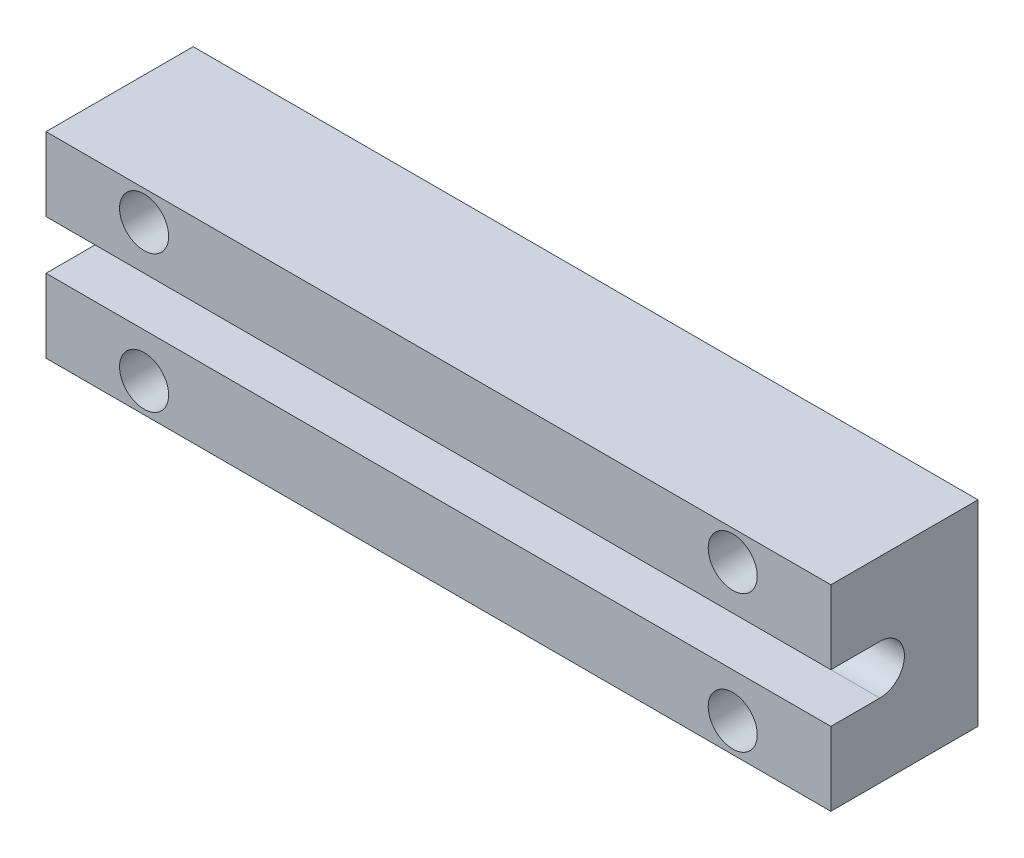
SolidWorks part; units mm, degrees
ref_plane "Plan de face" through (0, 0, 0) normal (0, 0, 1) x (1, 0, 0)
ref_plane "Plan de dessus" through (0, 0, 0) normal (0, 1, 0) x (1, 0, 0)
ref_plane "Plan de droite" through (0, 0, 0) normal (1, 0, 0) x (0, 0, -1)
sketch "Esquisse1" plane through (0, 0, 0) normal (0, 0, 1) x (1, 0, 0)
  line L1 (0, 0) -> (-80, 0)
  line L2 (0, 0) -> (0, 20)
  line L3 (0, 20) -> (-80, 20)
  line L4 (-80, 0) -> (-80, 20)
  dimension "D1" = 80
  dimension "D2" = 20
extrude "Boss.-Extru.1" add sketch "Esquisse1" along normal blind 15
sketch "Esquisse2" plane through (0, 0, 0) normal (1, 0, 0) x (0, 0, -1)
  line L0 (-15, 10) -> (-10, 10) construction
  line L1 (-15, 0) -> (-15, 20) construction
  line L2 (0, 0) -> (0, 20) construction
  line L3 (-7.5, 10) -> (0, 10) construction
  line L4 (-15, 7.5) -> (-10, 7.5)
  line L5 (-15, 7.5) -> (-15, 12.5)
  line L6 (-15, 12.5) -> (-10, 12.5)
  arc A0 (-10, 7.5) -> (-10, 12.5) centre (-10, 10) ccw
  dimension "D1" = 2.5
  dimension "D2" = 2.5
extrude "Enlèv. mat.-Extru.1" cut sketch "Esquisse2" against normal blind 94
sketch "Esquisse3" plane through (0, 0, 0) normal (0, 0, -1) x (-1, 0, 0)
  line L0 (40, 20) -> (40, 0) construction
  line L1 (0, 20) -> (80, 20) construction
  line L2 (80, 0) -> (0, 0) construction
  line L3 (10, 27.522) -> (10, -9.1433) construction
  line L4 (70, 25.7761) -> (70, -7.2726) construction
  circle A0 centre (10, 17) radius 2.5
  circle A1 centre (10, 3) radius 2.5
  circle A2 centre (70, 17) radius 2.5
  circle A3 centre (70, 3) radius 2.5
  dimension "D3" = 5
  dimension "D4" = 5
  dimension "D5" = 3
  dimension "D6" = 3
  dimension "D7" = 5
  dimension "D8" = 5
  dimension "D1" = 30
  dimension "D2" = 30
extrude "Enlèv. mat.-Extru.2" cut sketch "Esquisse3" against normal blind 94
